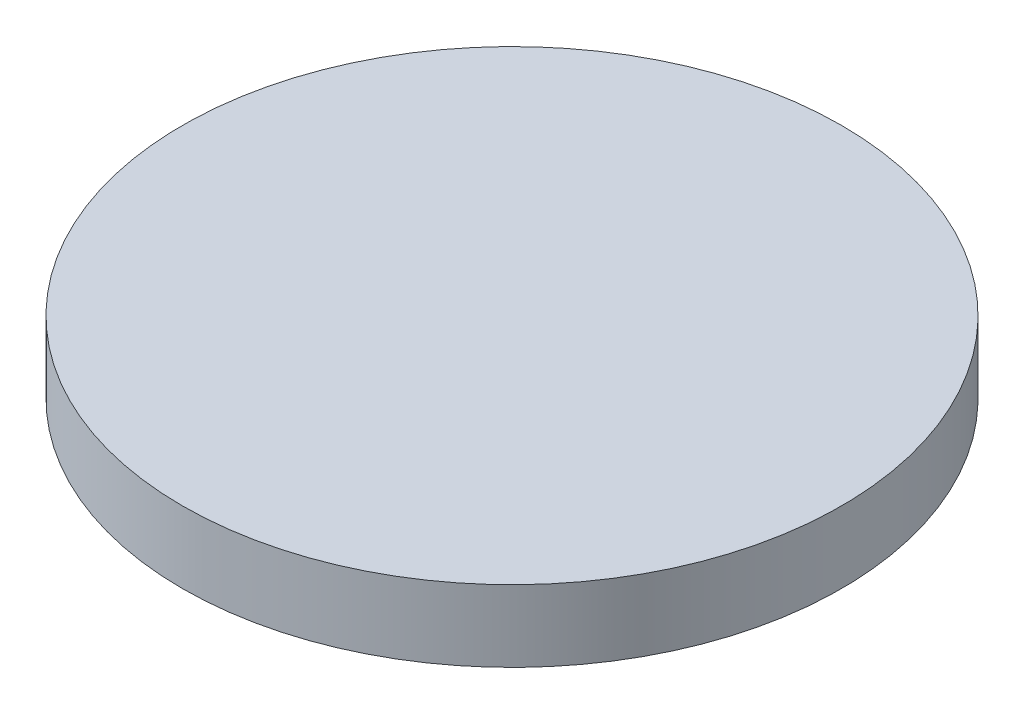
SolidWorks part; units mm, degrees
ref_plane "Front Plane" through (0, 0, 0) normal (0, 0, 1) x (1, 0, 0)
ref_plane "Top Plane" through (0, 0, 0) normal (0, 1, 0) x (1, 0, 0)
ref_plane "Right Plane" through (0, 0, 0) normal (1, 0, 0) x (0, 0, -1)
sketch "Sketch1" plane through (0, 0, 0) normal (0, 1, 0) x (1, 0, 0)
  circle A0 centre (0, 0) radius 4.6
  dimension "D1" = 9.2
extrude "Boss-Extrude1" add sketch "Sketch1" along normal blind 1
